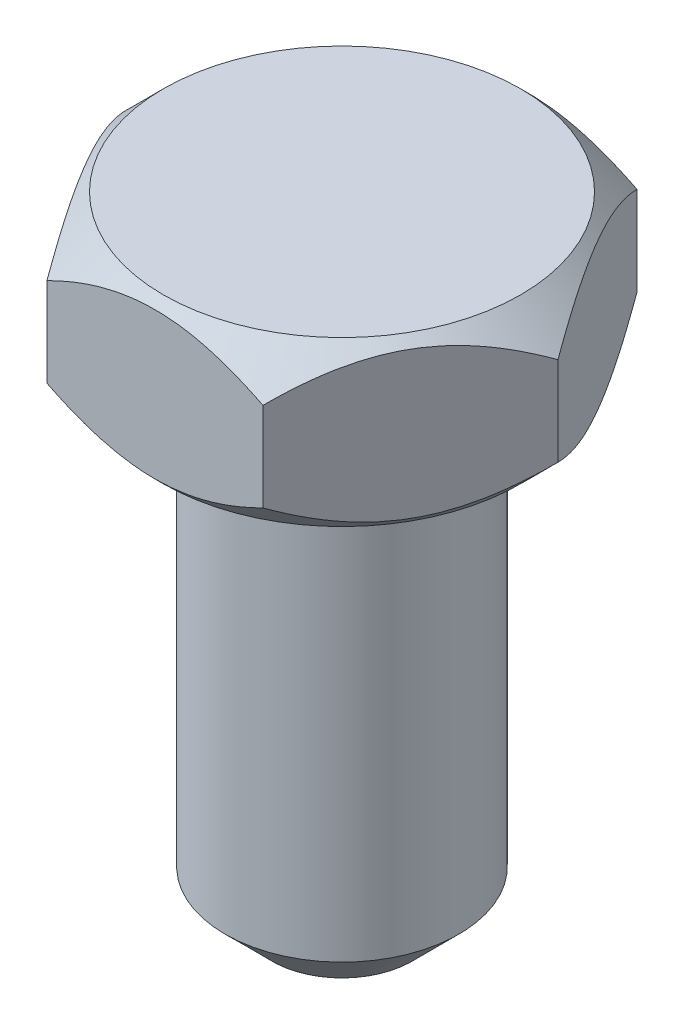
SolidWorks part; units mm, degrees
ref_plane "Спереди" through (0, 0, 0) normal (0, 0, 1) x (1, 0, 0)
ref_plane "Сверху" through (0, 0, 0) normal (0, 1, 0) x (1, 0, 0)
ref_plane "Справа" through (0, 0, 0) normal (1, 0, 0) x (0, 0, -1)
sketch "Эскиз1" plane through (0, 0, 0) normal (0, 1, 0) x (1, 0, 0)
  line L0 (-2.3094, 4) -> (2.3094, 4)
  line L1 (2.3094, 4) -> (4.6188, 0)
  line L2 (4.6188, 0) -> (2.3094, -4)
  line L3 (2.3094, -4) -> (-2.3094, -4)
  line L4 (-2.3094, -4) -> (-4.6188, 0)
  line L5 (-4.6188, 0) -> (-2.3094, 4)
  dimension "D5" = 4
  dimension "D2" = 120
  dimension "D3" = 120
  dimension "D4" = 120
  dimension "D6" = 4
  dimension "D7" = 4
  dimension "D8" = 4
  dimension "D9" = 4
  dimension "D10" = 120
  dimension "D11" = 4
extrude "Вытянуть1" add sketch "Эскиз1" against normal blind 3.5
sketch "Эскиз5" plane through (0, -3.5, 0) normal (0, -1, 0) x (1, 0, 0)
  circle A0 centre (0, 0) radius 2.5
  dimension "D1" = 5
extrude "Вытянуть2" add sketch "Эскиз5" along normal blind 10
chamfer "Фаска1" distance 1 angle 45 1 edges at (0, -13.5, -2.5)
ref_axis "Ось1" through (0, -3.5, 0) along (0, -1, 0)
ref_plane "Плоскость1" through (0, 0, 0) normal (0, 0, 1) x (1, 0, 0)
sketch "Эскиз4" plane through (0, 0, 0) normal (0, 0, 1) x (1, 0, 0)
  line L0 (-4.6188, -0.8) -> (-3.8188, 0)
  line L1 (-4.6188, -3.5) -> (-4.6188, 0) construction
  line L2 (-4.6188, 0) -> (-2.3094, 0) construction
  line L3 (-3.8188, 0) -> (-4.6188, 0)
  line L4 (-4.6188, 0) -> (-4.6188, -0.8)
  line L5 (-4.6188, -2.7) -> (-3.8188, -3.5)
  line L6 (-4.6188, -3.5) -> (-2.3094, -3.5) construction
  line L7 (-3.8188, -3.5) -> (-4.6188, -3.5)
  line L8 (-4.6188, -3.5) -> (-4.6188, -2.7)
  dimension "D1" = 0.8
  dimension "D2" = 0.8
  dimension "D3" = 0.8
  dimension "D4" = 0.8
revolve "Вырез-Повернуть1" cut sketch "Эскиз4" angle 360 about axis through (0, -3.5, 0) along (0, -1, 0)
